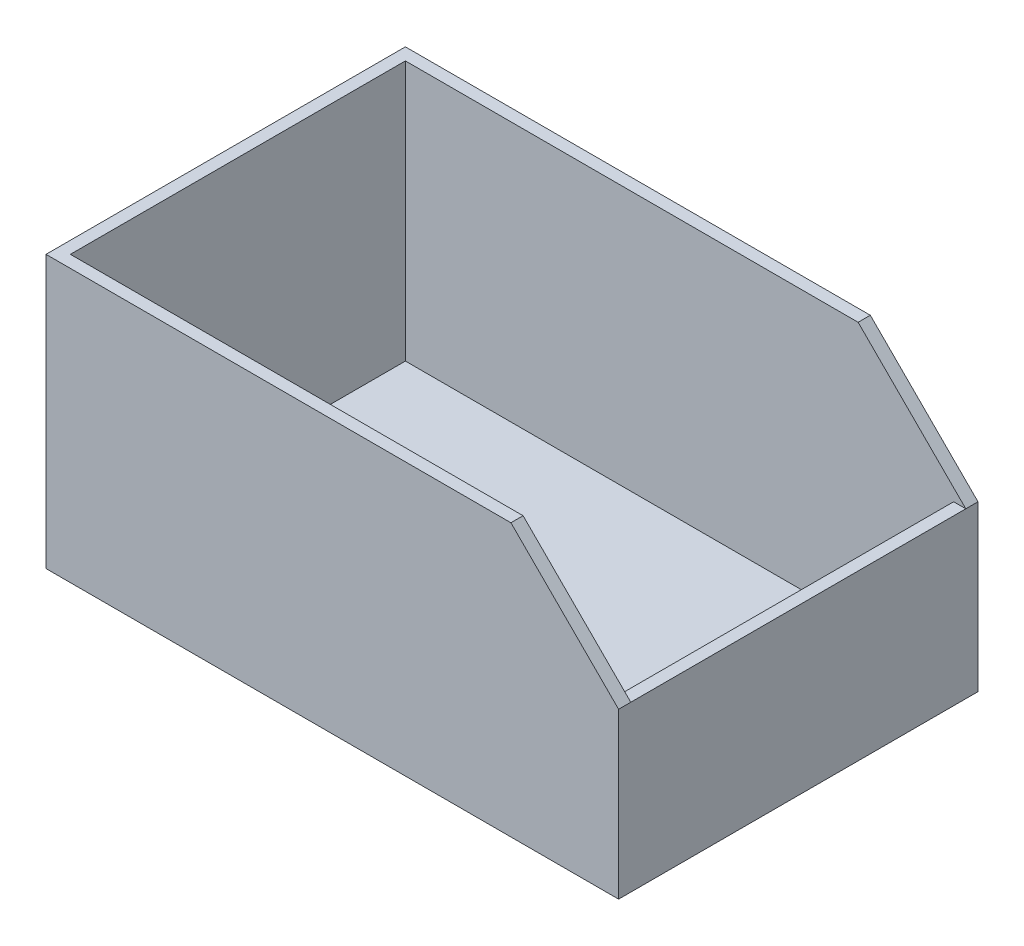
SolidWorks part; units mm, degrees
ref_plane "Front Plane" through (0, 0, 0) normal (0, 0, 1) x (1, 0, 0)
ref_plane "Top Plane" through (0, 0, 0) normal (0, 1, 0) x (1, 0, 0)
ref_plane "Right Plane" through (0, 0, 0) normal (1, 0, 0) x (0, 0, -1)
sketch "Sketch1" plane through (0, 0, 0) normal (0, 1, 0) x (1, 0, 0)
  line L0 (0, 55) -> (180, 55) construction
  line L1 (0, 0) -> (180, 0)
  line L2 (0, 0) -> (0, 110)
  line L3 (0, 110) -> (180, 110)
  line L4 (180, 0) -> (180, 110)
  dimension "D1" = 110
  dimension "D2" = 180
extrude "Boss-Extrude1" add sketch "Sketch1" along normal blind 4 contours L3 L4 L1 L2
sketch "Sketch3" plane through (180, 0, 0) normal (1, 0, 0) x (0, 0, -1)
  line L1 (0, 0) -> (110, 0)
  line L2 (0, 0) -> (0, 54)
  line L3 (0, 54) -> (110, 54)
  line L4 (110, 0) -> (110, 54)
  dimension "D1" = 50
extrude "Boss-Extrude2" add sketch "Sketch3" along normal blind 4 contours L4 L3 L2 L1
sketch "Sketch4" plane through (0, 0, -110) normal (0, 0, -1) x (-1, 0, 0)
  line L0 (-184, 54) -> (-148.6447, 89.3553)
  line L1 (-148.6447, 89.3553) -> (0, 89.3553)
  line L2 (0, 89.3553) -> (0, 4)
  line L3 (-184, 0) -> (-184, 54) construction
  line L8 (-180, 4) -> (-180, 54)
  line L9 (-180, 54) -> (-184, 54)
  line L10 (-184, 0) -> (0, 0)
  line L11 (0, 0) -> (0, 4)
  line L12 (0, 4) -> (-180, 4)
  line L15 (-184, 54) -> (-184, 0)
  line L16 (-184, 0) -> (0, 0)
  line L17 (0, 0) -> (0, 4)
  line L22 (-184, 54) -> (-184, 0)
  dimension "D1" = 135
  dimension "D2" = 50
  dimension "D3" = 0
extrude "Boss-Extrude3" add sketch "Sketch4" along normal blind 4
sketch "Sketch5" plane through (0, 0, 0) normal (-1, 0, 0) x (0, 0, 1)
  line L1 (-114, 89.3553) -> (0, 89.3553)
  line L2 (-114, 89.3553) -> (-114, 0)
  line L3 (-114, 0) -> (0, 0)
  line L4 (0, 89.3553) -> (0, 0)
extrude "Boss-Extrude4" add sketch "Sketch5" along normal blind 4 contours L1 L4 L3 L2
sketch "Sketch10" plane through (0, 0, 0) normal (0, 0, 1) x (1, 0, 0)
  line L0 (-4, 89.3553) -> (148.6447, 89.3553)
  line L1 (148.6447, 89.3553) -> (184, 54)
  line L2 (184, 54) -> (184, 0)
  line L3 (184, 0) -> (-4, 0)
  line L4 (-4, 0) -> (-4, 89.3553)
  point P4 (0, 0)
extrude "Boss-Extrude5" add sketch "Sketch10" along normal blind 4
